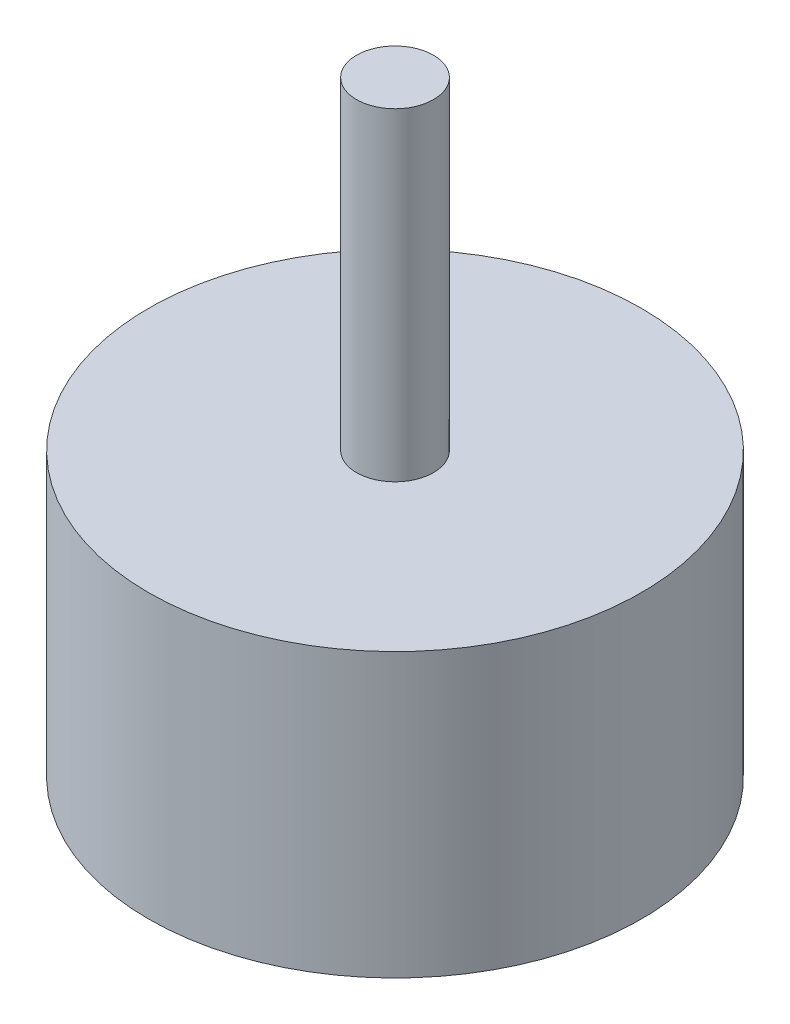
SolidWorks part; units mm, degrees
ref_plane "Plano frontal" through (0, 0, 0) normal (0, 0, 1) x (1, 0, 0)
ref_plane "Plano superior" through (0, 0, 0) normal (0, 1, 0) x (1, 0, 0)
ref_plane "Plano direito" through (0, 0, 0) normal (1, 0, 0) x (0, 0, -1)
sketch "Esboço1" plane through (0, 0, 0) normal (0, 0, 1) x (1, 0, 0)
  line L0 (0, 0) -> (0, 75)
  line L1 (0, 75) -> (-4.7625, 75)
  line L2 (-4.7625, 75) -> (-4.7625, 35)
  line L3 (-4.7625, 35) -> (-30.5, 35)
  line L4 (-30.5, 35) -> (-30.5, 0)
  line L5 (-30.5, 0) -> (0, 0)
  dimension "D1" = 30.5
  dimension "D2" = 35
  dimension "D3" = 4.7625
  dimension "D4" = 40
revolve "Revolução1" add sketch "Esboço1" angle 360 about L0
